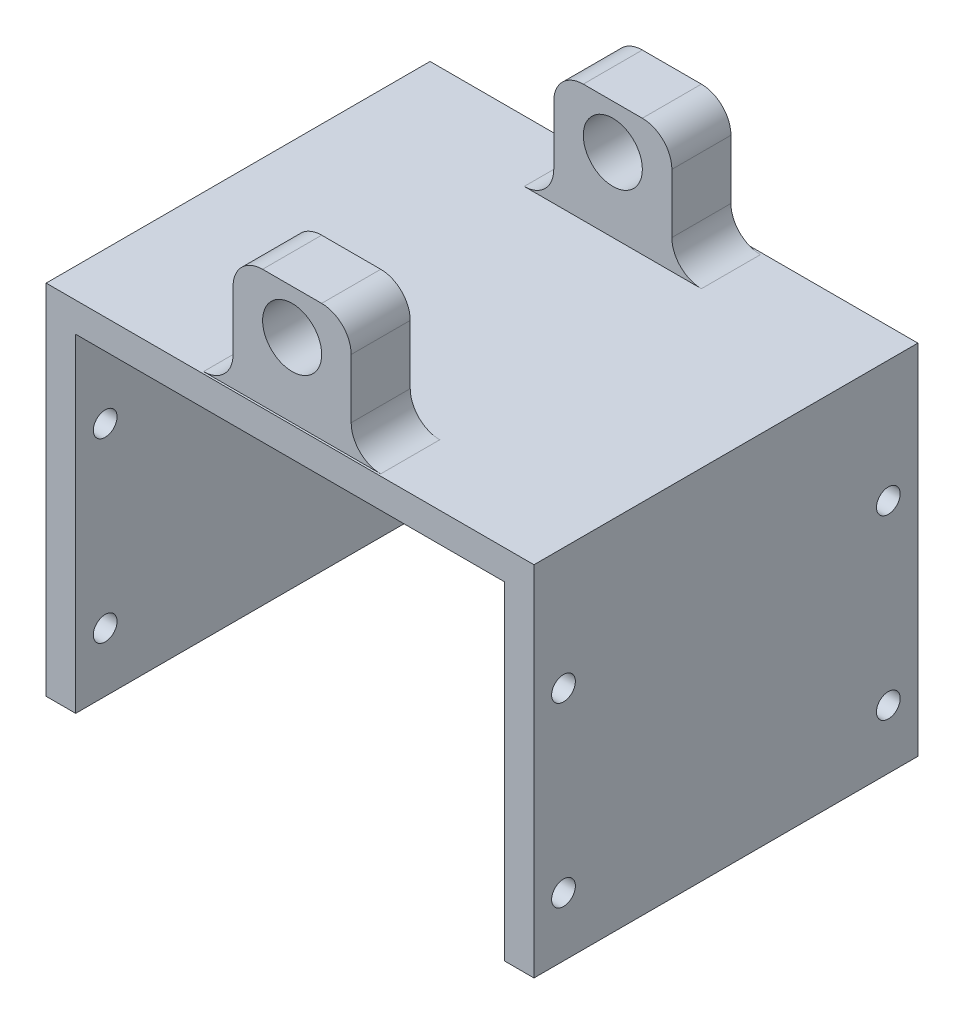
SolidWorks part; units mm, degrees
ref_plane "Front Plane" through (0, 0, 0) normal (0, 0, 1) x (1, 0, 0)
ref_plane "Top Plane" through (0, 0, 0) normal (0, 1, 0) x (1, 0, 0)
ref_plane "Right Plane" through (0, 0, 0) normal (1, 0, 0) x (0, 0, -1)
sketch "Sketch1" plane through (0, 0, 0) normal (0, 0, 1) x (1, 0, 0)
  line L0 (98.552, 0) -> (104.902, 0)
  line L1 (0, 76.962) -> (104.902, 76.962)
  line L2 (0, 76.962) -> (0, 0)
  line L3 (0, 0) -> (6.35, 0)
  line L4 (104.902, 76.962) -> (104.902, 0)
  line L5 (6.35, 70.612) -> (98.552, 70.612)
  line L6 (6.35, 70.612) -> (6.35, 0)
  line L8 (98.552, 70.612) -> (98.552, 0)
  line L9 (39.751, 102.362) -> (65.151, 102.362)
  line L10 (39.751, 102.362) -> (39.751, 76.962)
  line L11 (39.751, 76.962) -> (65.151, 76.962)
  line L12 (65.151, 102.362) -> (65.151, 76.962)
  circle A0 centre (52.451, 92.837) radius 6.35
  dimension "D11" = 12.7
  dimension "D1" = 92.202
  dimension "D2" = 70.612
  dimension "D3" = 6.35
  dimension "D4" = 6.35
  dimension "D5" = 6.35
  dimension "D6" = 25.4
  dimension "D7" = 33.401
  dimension "D8" = 25.4
  dimension "D9" = 9.525
  dimension "D10" = 12.7
extrude "Boss-Extrude1" add sketch "Sketch1" along normal blind 82.55 contours L12 L9 L10 L1 A0 | L5 L8 L0 L4 L1 L2 L3 L6
fillet "Fillet1" radius 6.35 4 edges at (65.151, 76.962, 41.275) (39.751, 76.962, 41.275) (39.751, 102.362, 41.275) (65.151, 102.362, 41.275)
ref_plane "Plane1" through (0, 108.712, 0) normal (0, 1, 0) x (1, 0, 0)
sketch "Sketch3" plane through (0, 108.712, 0) normal (0, 1, 0) x (1, 0, 0)
  line L0 (0, -82.55) -> (33.401, -82.55) construction
  line L1 (-11.726, -82.1055) -> (124.8825, -82.1055)
  line L2 (-11.726, -69.4055) -> (-11.726, -13.1445)
  line L3 (-11.726, -13.1445) -> (124.8825, -13.1445)
  line L4 (124.8825, -69.4055) -> (124.8825, -13.1445)
  line L5 (124.8825, -0.4445) -> (-11.726, -0.4445)
  line L6 (124.8825, -13.1445) -> (124.8825, -69.4055)
  line L7 (124.8825, -69.4055) -> (-11.726, -69.4055)
  line L8 (-11.726, -13.1445) -> (-11.726, -69.4055)
  line L10 (-11.726, -82.1055) -> (124.8825, -82.1055)
  line L11 (-11.726, -82.1055) -> (-11.726, -106.365)
  line L12 (-11.726, -106.365) -> (124.8825, -106.365)
  line L13 (124.8825, -82.1055) -> (124.8825, -106.365)
  line L14 (-11.726, -0.4445) -> (124.8825, -0.4445)
  line L15 (-11.726, -0.4445) -> (-11.726, 27.3507)
  line L16 (-11.726, 27.3507) -> (124.8825, 27.3507)
  line L17 (124.8825, -0.4445) -> (124.8825, 27.3507)
  dimension "D1" = 68.961
  dimension "D2" = 68.961
  dimension "D3" = 12.7
  dimension "D4" = 0.4445
extrude "Cut-Extrude3" cut sketch "Sketch3" against normal blind 31.75 contours L5 L17 L16 L15 | L7 L4 L3 L2 | L13 L1 L11 L12
sketch "Sketch4" plane through (0, 0, 0) normal (-1, 0, 0) x (0, 0, 1)
  line L1 (0, 76.962) -> (0, 0) construction
  line L2 (82.55, 0) -> (0, 0) construction
  circle A0 centre (6.35, 50.8) radius 2.5527
  circle A1 centre (76.2, 50.8) radius 2.5527
  circle A2 centre (76.2, 12.7) radius 2.5527
  circle A3 centre (6.35, 12.7) radius 2.5527
  dimension "D1" = 5.1054
  dimension "D2" = 69.85
  dimension "D3" = 6.35
  dimension "D4" = 12.7
  dimension "D5" = 50.8
hole_wizard "Tap Drill for 1/4-20 Tap1" positions "Sketch6" profile "Sketch5" hole size "1/4-20" standard "ANSI Inch" end condition through all
sketch "Sketch6" plane through (0, 0, 0) normal (-1, 0, 0) x (0, 0, 1)
  point P0 (6.35, 50.8)
  point P3 (6.35, 12.7)
  point P6 (76.2, 12.7)
  point P9 (76.2, 50.8)
sketch "Sketch5" plane through (0, 50.8, 6.35) normal (0, 1, 0) x (0, 0, 1)
  line L0 (0, 0) -> (0, 104.902)
  line L1 (0, 104.902) -> (2.5527, 104.902)
  line L2 (2.5527, 104.902) -> (2.5527, 0)
  line L5 (2.5527, 0) -> (0, 0)
  line L11 (0, -6.35) -> (0, 107.95) construction
  dimension "Thru Hole Dia." = 5.1054
  dimension "Thru Hole Depth" = 104.902
